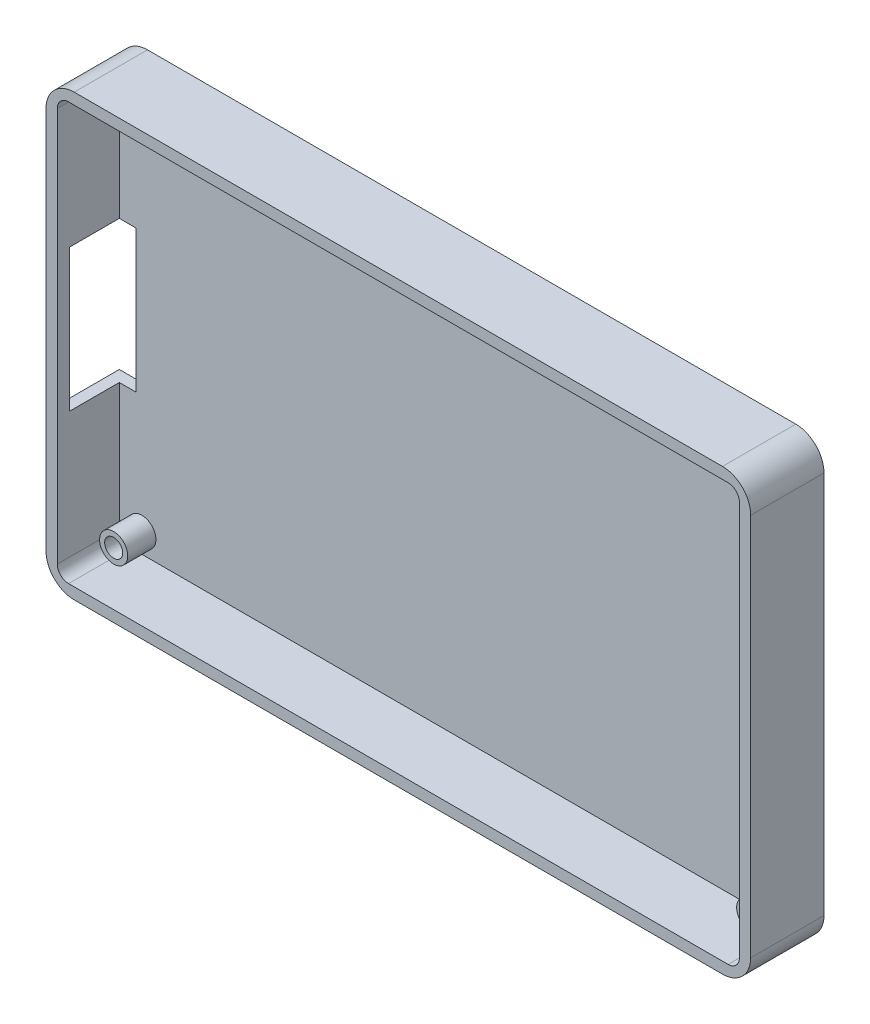
SolidWorks part; units mm, degrees
ref_plane "Front Plane" through (0, 0, 0) normal (0, 0, 1) x (1, 0, 0)
ref_plane "Top Plane" through (0, 0, 0) normal (0, 1, 0) x (1, 0, 0)
ref_plane "Right Plane" through (0, 0, 0) normal (1, 0, 0) x (0, 0, -1)
sketch "草图1" plane through (0, 0, 0) normal (0, 0, 1) x (1, 0, 0)
  line L0 (0, 0) -> (-48.2403, 0) construction
  line L1 (-62.5, 39) -> (62.5, 39)
  line L2 (-62.5, 39) -> (-62.5, -39)
  line L3 (-62.5, -39) -> (62.5, -39)
  line L4 (62.5, 39) -> (62.5, -39)
  line L5 (-62.5, 39) -> (62.5, -39) construction
  line L6 (-62.5, -39) -> (62.5, 39) construction
  line L7 (-60, 37) -> (60, 37)
  line L8 (-60, 37) -> (-60, -37)
  line L9 (-60, -37) -> (60, -37)
  line L10 (60, 37) -> (60, -37)
  line L11 (-60, 37) -> (60, -37) construction
  line L12 (-60, -37) -> (60, 37) construction
  line L13 (0, 0) -> (0, 21.3653) construction
  circle A0 centre (-57, 33.5) radius 1.6 construction
  circle A1 centre (-57, 33.5) radius 3.6 construction
  circle A2 centre (-57, -33.5) radius 1.6 construction
  circle A3 centre (-57, -33.5) radius 3.6 construction
  circle A4 centre (57, -33.5) radius 3.6 construction
  circle A5 centre (57, -33.5) radius 1.6 construction
  circle A6 centre (57, 33.5) radius 3.6 construction
  circle A7 centre (57, 33.5) radius 1.6 construction
  point P0 (0, 0)
  point P6 (0, 0)
  dimension "D5" = 3.2
  dimension "D1" = 125
  dimension "D2" = 78
  dimension "D3" = 120
  dimension "D4" = 74
  dimension "D7" = 33.5
  dimension "D8" = 57
  dimension "D6" = 2
extrude "凸台-拉伸1" add sketch "草图1" along normal blind 13 contours L4 L1 L2 L3 A3 A1 A4 A6 | A6 A7 | A3 A2 | A4 A5 | A1 A0 | L10 L7 L8 L9
shell "抽壳1" thickness 2
sketch "草图3" plane through (0, 0, 2) normal (0, 0, 1) x (1, 0, 0)
  line L0 (0, 0) -> (-35.4135, 0) construction
  line L1 (0, 0) -> (0, 18.0663) construction
  circle A0 centre (-56.5, 33.5) radius 2.5
  circle A1 centre (-56.5, 33.5) radius 1.6
  circle A2 centre (56.5, 33.5) radius 2.5
  circle A3 centre (56.5, 33.5) radius 1.6
  circle A4 centre (56.5, -33.5) radius 1.6
  circle A5 centre (56.5, -33.5) radius 2.5
  circle A6 centre (-56.5, -33.5) radius 1.6
  circle A7 centre (-56.5, -33.5) radius 2.5
  dimension "D1" = 3.2
  dimension "D2" = 5
  dimension "D3" = 56.5
  dimension "D4" = 33.5
extrude "凸台-拉伸2" add sketch "草图3" along normal blind 5
sketch "草图4" plane through (0, 0, 2) normal (0, 0, 1) x (1, 0, 0)
  line L0 (0, 0) -> (-24.0884, 0) construction
  line L1 (0, 0) -> (0, 10.2465) construction
sketch "草图5" plane through (-62.5, 0, 0) normal (-1, 0, 0) x (0, 0, 1)
  line L0 (6.5, 39) -> (6.5, -39) construction
  line L1 (13, 39) -> (0, 39) construction
  line L2 (13, -39) -> (0, -39) construction
  line L3 (0, 39) -> (0, -39) construction
  line L4 (2.1384, 12.6032) -> (10.8616, 12.6032)
  line L6 (2.1384, -12.6032) -> (10.8616, -12.6032)
  line L7 (10.8616, 12.6032) -> (10.8616, -12.6032)
  line L8 (2.1384, 12.6032) -> (10.8616, -12.6032) construction
  line L9 (2.1384, -12.6032) -> (10.8616, 12.6032) construction
  line L10 (2.1384, 12.6032) -> (0, 12.6032)
  line L12 (2.1384, -12.6032) -> (0, -12.6032)
  line L13 (0, 12.6032) -> (0, -12.6032)
  point P6 (6.5, 0)
extrude "切除-拉伸1" cut sketch "草图5" against normal blind 5
sketch "草图6" plane through (0, 39, 0) normal (0, 1, 0) x (1, 0, 0)
  line L0 (0, 0) -> (0, -13) construction
  line L1 (-62.5, -13) -> (62.5, -13) construction
  line L3 (-27.3918, -13) -> (18.2083, -13)
  line L4 (-27.3918, -13) -> (-27.3918, 21.5708)
  line L5 (-27.3918, 21.5708) -> (18.2083, 21.5708)
  line L6 (18.2083, -13) -> (18.2083, 21.5708)
  circle A0 centre (23, 12) radius 1.6
  circle A1 centre (-25, 12) radius 1.6
  dimension "D1" = 3.2
  dimension "D2" = 3.2
fillet "圆角1" radius 5 4 edges at (62.5, -39, 6.5) (-62.5, -39, 6.5) (-62.5, 39, 6.5) (62.5, 39, 6.5)
fillet "圆角2" radius 2 4 edges at (60.5, 37, 7.5) (60.5, -37, 7.5) (-60.5, -37, 7.5) (-60.5, 37, 7.5)
sketch "草图8" plane through (0, 0, 13) normal (0, 0, 1) x (1, 0, 0)
  line L4 (-57.5, -39) -> (57.5, -39)
  line L5 (-57.5, -39) -> (57.5, -39)
  line L6 (62.5, -34) -> (62.5, 34)
  line L7 (62.5, -34) -> (62.5, 34)
  line L12 (57.5, 39) -> (-57.5, 39)
  line L13 (57.5, 39) -> (-57.5, 39)
  line L14 (-62.5, 34) -> (-62.5, -34)
  line L15 (-62.5, 34) -> (-62.5, -34)
  arc A4 (57.5, -39) -> (62.5, -34) centre (57.5, -34) ccw
  arc A5 (57.5, -39) -> (62.5, -34) centre (57.5, -34) ccw
  arc A6 (62.5, 34) -> (57.5, 39) centre (57.5, 34) ccw
  arc A7 (62.5, 34) -> (57.5, 39) centre (57.5, 34) ccw
  arc A8 (-57.5, 39) -> (-62.5, 34) centre (-57.5, 34) ccw
  arc A9 (-57.5, 39) -> (-62.5, 34) centre (-57.5, 34) ccw
  arc A10 (-62.5, -34) -> (-57.5, -39) centre (-57.5, -34) ccw
  arc A11 (-62.5, -34) -> (-57.5, -39) centre (-57.5, -34) ccw
  dimension "D1" = 0
